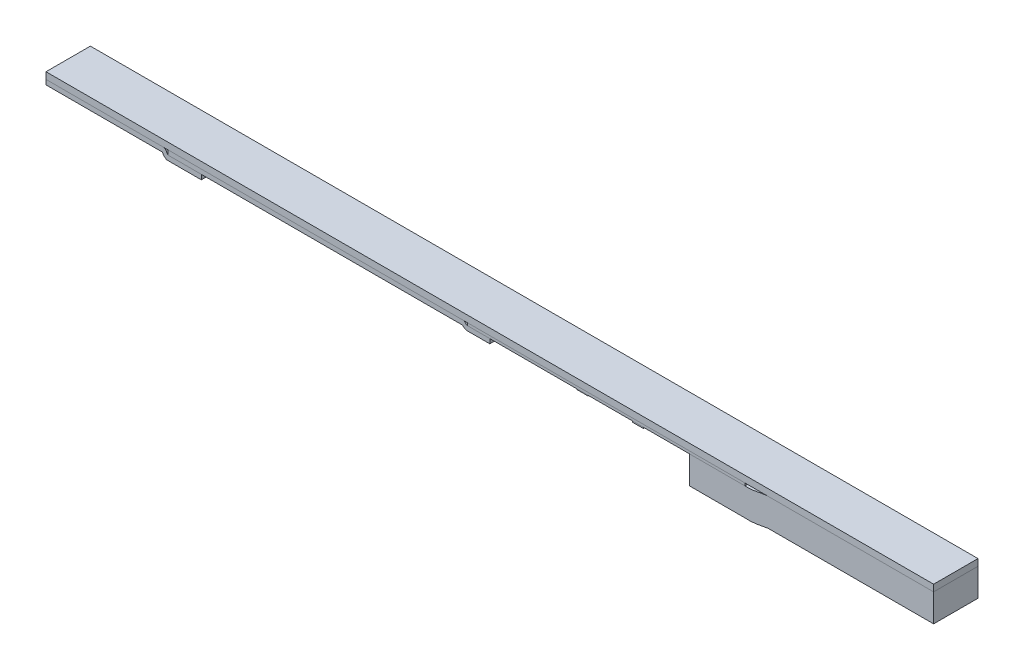
SolidWorks part; units mm, degrees
other "ExplView1" [suppressed]
other "Explode Step1" [suppressed]
other "Explode Line1"
other "Explode Step2" [suppressed]
other "Explode Line1"
other "Explode Line2"
other "Explode Step3" [suppressed]
other "Explode Line1"
other "Explode Step4" [suppressed]
other "Explode Line1"
other "Explode Step5" [suppressed]
other "Explode Line1"
other "Explode Line2"
other "Explode Line3"
ref_plane "Front" through (0, 0, 0) normal (0, 0, 1) x (1, 0, 0)
ref_plane "Top" through (0, 0, 0) normal (0, 1, 0) x (1, 0, 0)
ref_plane "Right" through (0, 0, 0) normal (1, 0, 0) x (0, 0, -1)
sketch "Sketch1" plane through (0, 0, 0) normal (0, 1, 0) x (1, 0, 0)
  line L1 (-40, -2) -> (40, -2)
  line L2 (-40, -2) -> (-40, 2)
  line L3 (-40, 2) -> (40, 2)
  line L4 (40, -2) -> (40, 2)
  line L5 (-40, -2) -> (40, 2) construction
  line L6 (-40, 2) -> (40, -2) construction
  point P0 (0, 0)
  dimension "D1" = 80
  dimension "D2" = 4
extrude "80mm backing card" add sketch "Sketch1" along normal blind 0.6
ref_plane "Middle downstream axis strip" through (0, 0, 0) normal (0, 0, 1) x (1, 0, 0)
sketch "Sketch18" plane through (0, 0, 0) normal (0, -1, 0) x (1, 0, 0)
  line L2 (-2, 2) -> (23, 2)
  line L3 (-2, 2) -> (-2, -2)
  line L4 (-2, -2) -> (23, -2)
  line L5 (23, 2) -> (23, -2)
  line L6 (40, -2) -> (-40, -2) construction
  line L7 (40, 2) -> (40, -2) construction
  dimension "D1" = 25
  dimension "D2" = 17
extrude "CN95_25mm_17mm from end" add sketch "Sketch18" along normal blind 0.23 separate body
sketch "Sketch3" plane through (0, 0, 0) normal (0, -1, 0) x (1, 0, 0)
  line L0 (0, 0) -> (19, 0) construction
  line L1 (-6, -2) -> (19, -2)
  line L2 (-6, -2) -> (-6, 2)
  line L3 (-6, 2) -> (19, 2)
  line L4 (19, -2) -> (19, 2)
  line L5 (-6, -2) -> (19, 2) construction
  line L6 (-6, 2) -> (19, -2) construction
  point P0 (10.5, 0)
  dimension "D1" = 10.5
  dimension "D2" = 25
  dimension "D3" = 4
  dimension "D4" = 19
extrude "CN95_25mm" [suppressed] add sketch "Sketch3" along normal blind 0.23 separate body
sketch "Sketch8" [suppressed] plane through (0, 0, 0) normal (0, 0, 1) x (1, 0, 0)
  line L1 (14, -1.03) -> (18.843, -1.03)
  line L2 (14, -1.03) -> (14, -0.23)
  line L3 (19.6805, 0) -> (40, 0)
  line L4 (14, -0.23) -> (19, -0.23)
  line L5 (40, -0.8) -> (40, 0)
  line L6 (19.8592, -0.8) -> (40, -0.8)
  line L8 (14.8, -1.03) -> (18.843, -1.03) construction
  line L9 (19.8592, -0.8) -> (39.2, -0.8) construction
  line L10 (0, 0) -> (14, 0) construction
  line L11 (-6, -0.23) -> (19, -0.23) construction
  line L12 (39.2, -0.8) -> (39.2, -0.8) construction
  line L13 (14.8, -1.03) -> (14.8, -1.03) construction
  spline S0 degree 3 poles (19, -0.23) (19.3285, -0.4198) (19.391, 0.0213) (19.6805, 0) knots 0 0 0 0 1 1 1 1
  spline S1 degree 1 poles (18.843, -1.03) (19.8592, -0.8) knots 0 0 1 1 construction
  spline S2 degree 3 poles (18.843, -1.03) (18.9476, -1.0624) (19.167, -1.0968) (19.5027, -1.0322) (19.7371, -0.9006) (19.8143, -0.8386) (19.8592, -0.8) knots 0.086652 0.086652 0.086652 0.086652 0.182115 0.277578 0.373041 0.468503 0.468503 0.468503 0.468503
  dimension "D1" = 0.8
  dimension "D2" = 14
  dimension "D3" = 0
  dimension "D4" = 21
extrude "C083_26mm" [suppressed] add sketch "Sketch8" against normal up to vertex and the other way up to vertex separate body
sketch "Sketch10" [suppressed] plane through (0, 0, 0) normal (0, 0, 1) x (1, 0, 0)
  line L0 (-4, 0) -> (-29, 0) construction
  line L1 (-6.4051, 0) -> (-29, 0)
  line L2 (-4, -0.23) -> (-6, -0.23)
  line L3 (-4, -0.53) -> (-5.9863, -0.53)
  line L4 (-6.4562, -0.3) -> (-29, -0.3)
  line L5 (-4, -0.53) -> (-4, -0.23)
  line L6 (-6, -0.23) -> (19, -0.23) construction
  line L7 (-29, -0.3) -> (-29, 0)
  spline S0 degree 3 poles (-6, -0.23) (-6.1991, -0.2528) (-6.2203, -0.0102) (-6.4051, 0) knots 0 0 0 0 1 1 1 1
  spline S1 degree 1 poles (-5.9863, -0.53) (-6.4562, -0.3) knots 0 0 1 1 construction
  spline S2 degree 3 poles (-5.9863, -0.53) (-6.1018, -0.5388) (-6.3067, -0.4635) (-6.4147, -0.3458) (-6.4399, -0.3178) (-6.4562, -0.3) knots 0.015374 0.015374 0.015374 0.015374 0.30052 0.443093 0.585666 0.585666 0.585666 0.585666
  dimension "D1" = 25
  dimension "D2" = 0
  dimension "D3" = 2
  dimension "D4" = 0.3
extrude "F5_25mm" [suppressed] add sketch "Sketch10" along normal up to vertex and the other way up to vertex separate body
sketch "Sketch11" plane through (0, 0, 0) normal (0, -1, 0) x (1, 0, 0)
  line L0 (40, -2) -> (-40, -2) construction
  line L1 (-40, 2) -> (-33, 2)
  line L2 (-40, 2) -> (-40, -2)
  line L3 (-40, -2) -> (-33, -2)
  line L4 (-33, 2) -> (-33, -2)
  dimension "D1" = 7
extrude "CN95 sample pad_7mm" [suppressed] add sketch "Sketch11" along normal blind 0.82 separate body
sketch "Sketch12" plane through (0, 0, 0) normal (0, 0, 1) x (1, 0, 0)
  line L0 (0, 0) -> (-32.1741, 0) construction
  line L1 (0, 0) -> (-27, 0) construction
  line L2 (-32.1741, 0) -> (-30.0838, 0)
  line L3 (-27, -1.3) -> (-29, -1.3)
  line L4 (-35, -0.82) -> (-33, -0.82)
  line L5 (-35, -1.56) -> (-32.97, -1.56)
  line L6 (-31.9067, -0.74) -> (-30.2503, -0.74)
  line L7 (-27, -2.04) -> (-29.0406, -2.04)
  line L8 (-35, -1.56) -> (-35, -0.82)
  line L9 (-27, -2.04) -> (-27, -1.3)
  spline S0 degree 3 poles (-33, -0.82) (-32.4851, -0.7782) (-32.6673, -0.0946) (-32.1741, 0) knots 0 0 0 0 1 1 1 1
  spline S1 degree 3 poles (-29, -1.3) (-29.7084, -1.2221) (-29.2786, -0.0898) (-30.0838, 0) knots 0 0 0 0 1 1 1 1
  spline S2 degree 1 poles (-32.97, -1.56) (-31.9067, -0.74) knots 0 0 1 1 construction
  spline S3 degree 1 poles (-29.0406, -2.04) (-30.2503, -0.74) knots 0 0 1 1 construction
  spline S4 degree 3 poles (-32.97, -1.56) (-32.9619, -1.5593) (-32.9526, -1.5587) (-32.8787, -1.5522) (-32.7475, -1.5311) (-32.4851, -1.4502) (-32.1734, -1.22) (-31.9863, -0.9229) (-31.9366, -0.8093) (-31.9067, -0.74) knots -0.019337 -0.019337 -0.019337 -0.019337 -0.003586 0.012164 0.043666 0.106669 0.232675 0.358681 0.484687 0.484687 0.484687 0.484687
  spline S5 degree 3 poles (-30.2503, -0.74) (-30.2392, -0.7763) (-30.2216, -0.8412) (-30.1686, -1.0392) (-30.0916, -1.2954) (-29.8973, -1.6109) (-29.6588, -1.8425) (-29.3828, -1.9746) (-29.1974, -2.0206) (-29.0668, -2.0376) (-29.0537, -2.0386) (-29.0406, -2.04) knots -0.018979 -0.018979 -0.018979 -0.018979 0.054899 0.128777 0.276534 0.350412 0.424291 0.498169 0.535108 0.553578 0.572048 0.572048 0.572048 0.572048
  dimension "D1" = 0.74
  dimension "D2" = 27
  dimension "D3" = 1.3
  dimension "D4" = 2
  dimension "D6" = 2
extrude "Shunt" [suppressed] add sketch "Sketch12" along normal up to vertex and the other way up to vertex separate body
sketch "Sketch13" [suppressed] plane through (0, 0, 0) normal (0, 0, 1) x (1, 0, 0)
  line L0 (-29, -0.3) -> (-6.4562, -0.3) construction
  line L1 (0, 0) -> (-26, 0) construction
  line L2 (-26, -0.64) -> (-29.1253, -0.64)
  line L3 (-40, -0.34) -> (-29.4516, -0.34)
  line L4 (-40, 0) -> (-29.3869, 0)
  line L5 (-29.3869, 0) -> (-40, 0) construction
  line L6 (-26, -0.3) -> (-29, -0.3)
  line L7 (-26, -0.64) -> (-26, -0.3)
  line L8 (-40, -0.34) -> (-40, 0)
  spline S0 degree 3 poles (-29, -0.3) (-29.1238, -0.1944) (-29.2189, -0.0439) (-29.3869, 0) knots 0 0 0 0 1 1 1 1
  spline S1 degree 1 poles (-29.1253, -0.64) (-29.4516, -0.34) knots 0 0 1 1 construction
  spline S2 degree 3 poles (-29.1253, -0.64) (-29.1555, -0.6142) (-29.2081, -0.572) (-29.3337, -0.4528) (-29.4092, -0.3732) (-29.434, -0.352) (-29.4516, -0.34) knots -0.25657 -0.25657 -0.25657 -0.25657 -0.012563 0.231444 0.475452 0.719459 0.719459 0.719459 0.719459
  dimension "D1" = 26
  dimension "D2" = 14
  dimension "D3" = 0
  dimension "D4" = 3
  dimension "D5" = 0.34
extrude "CF3_14mm" [suppressed] add sketch "Sketch13" along normal up to vertex and the other way up to vertex separate body
ref_plane "Plane2" through (0, 0, 0) normal (1, 0, 0) x (0, 0, -1)
sketch "Sketch16" plane through (0, 0, 0) normal (0, 0, 1) x (1, 0, 0)
  line L0 (0, 0) -> (-26, 0) construction
  line L1 (-26, 0) -> (-26, -0.41) construction
  line L2 (-26, -0.41) -> (-29, -0.41)
  line L3 (-40, 0) -> (-29.42, 0)
  line L4 (-40, -0.43) -> (-29.5129, -0.43)
  line L5 (-26, -0.84) -> (-29.149, -0.84)
  line L6 (-40, -0.43) -> (-40, 0)
  line L7 (-26, -0.84) -> (-26, -0.41)
  spline S0 degree 3 poles (-29, -0.41) (-29.157, -0.2864) (-29.1646, 0.0012) (-29.42, 0) knots 0 0 0 0 1 1 1 1
  spline S1 degree 1 poles (-29.149, -0.84) (-29.5129, -0.43) knots 0 0 1 1 construction
  spline S2 degree 3 poles (-29.5129, -0.43) (-29.493, -0.4661) (-29.4596, -0.5264) (-29.3746, -0.6553) (-29.2481, -0.7632) (-29.218, -0.7849) (-29.1737, -0.8205) (-29.149, -0.84) knots -0.248578 -0.248578 -0.248578 -0.248578 -0.091181 0.066215 0.144914 0.223612 0.381008 0.381008 0.381008 0.381008
  dimension "D1" = 26
  dimension "D2" = 0.41
  dimension "D3" = 3
  dimension "D4" = 10.58
  dimension "D5" = 40
  dimension "D6" = 0.43
extrude "CF4_14mm" add sketch "Sketch16" along normal up to vertex and the other way up to vertex separate body
sketch "Sketch17" plane through (0, 0, 0) normal (0, 0, 1) x (1, 0, 0)
  line L0 (0, 0) -> (18, 0) construction
  line L1 (25, 0) -> (40, 0)
  line L2 (18, 0) -> (18, -0.185) construction
  line L3 (18, -0.185) -> (23, -0.185)
  line L4 (18, -2.685) -> (22.7601, -2.685)
  line L5 (25.0293, -2.5) -> (40, -2.5)
  line L6 (18, -2.685) -> (18, -0.185)
  line L7 (40, -2.5) -> (40, 0)
  spline S0 degree 3 poles (23, -0.185) (23.6752, -0.3602) (24.3288, -0.0019) (25, 0) knots 0 0 0 0 1 1 1 1
  spline S1 degree 1 poles (22.7601, -2.685) (25.0293, -2.5) knots 0 0 1 1 construction
  spline S2 degree 3 poles (22.7601, -2.685) (22.9258, -2.7107) (23.275, -2.741) (23.8617, -2.7229) (24.4384, -2.6271) (24.7976, -2.5436) (24.9779, -2.5078) (25.0069, -2.503) (25.0293, -2.5) knots 0.070736 0.070736 0.070736 0.070736 0.168218 0.2657 0.460665 0.655629 0.753112 0.850594 0.850594 0.850594 0.850594
  dimension "D1" = 18
  dimension "D2" = 15
  dimension "D3" = 40
  dimension "D4" = 0.185
  dimension "D5" = 5
  dimension "D6" = 2.5
extrude "Alstrohm 320_22mm_w HF90" [suppressed] add sketch "Sketch17" along normal up to vertex and the other way up to vertex separate body
sketch "Sketch19" plane through (0, 0, 0) normal (0, 0, 1) x (1, 0, 0)
  line L0 (0, 0) -> (-29, 0) construction
  line L1 (0, 0) -> (0, -0.23) construction
  line L2 (0, -0.23) -> (-2, -0.23)
  line L3 (-29, 0) -> (-2.3642, 0)
  line L4 (0, -0.64) -> (-2.0338, -0.64)
  line L5 (-29, -0.41) -> (-2.4794, -0.41)
  line L6 (0, -0.64) -> (0, -0.23)
  line L7 (-29, -0.41) -> (-29, 0)
  spline S0 degree 3 poles (-2, -0.23) (-2.1507, -0.205) (-2.2224, -0.046) (-2.3642, 0) knots 0 0 0 0 1 1 1 1
  spline S1 degree 1 poles (-2.0338, -0.64) (-2.4794, -0.41) knots 0 0 1 1 construction
  spline S2 degree 3 poles (-2.0338, -0.64) (-2.0473, -0.6378) (-2.0578, -0.6377) (-2.2098, -0.6021) (-2.3207, -0.5396) (-2.4258, -0.4595) (-2.4586, -0.4286) (-2.4794, -0.41) knots -0.073801 -0.073801 -0.073801 -0.073801 0.00573 0.085261 0.244322 0.403384 0.562446 0.562446 0.562446 0.562446
  dimension "D1" = 29
  dimension "D2" = 0.23
  dimension "D3" = 2
  dimension "D4" = 26.6358
  dimension "D5" = 0.41
extrude "GFDX_29mm" add sketch "Sketch19" along normal up to vertex and the other way up to vertex separate body
fillet "Fillet2" [suppressed] radius 0.254
sketch "Sketch20" [suppressed] plane through (0, -0.43, 0) normal (0, -1, 0) x (1, 0, 0)
  text T0 "CF4" font "Century Gothic" height in points 10
extrude "Cut-Extrude1" [suppressed] cut sketch "Sketch20" against normal blind 0.0254
sketch "Sketch21" [suppressed] plane through (0, -0.41, 0) normal (0, -1, 0) x (1, 0, 0)
  text T0 "GFDX" font "Century Gothic" height in points 10
extrude "Cut-Extrude2" [suppressed] cut sketch "Sketch21" against normal blind 0.0254
sketch "Sketch22" [suppressed] plane through (0, -0.23, 0) normal (0, -1, 0) x (1, 0, 0)
  text T0 "CN95" font "Century Gothic" height in points 10
extrude "Cut-Extrude3" [suppressed] cut sketch "Sketch22" against normal blind 0.0254
sketch "Sketch23" [suppressed] plane through (0, -2.5, 0) normal (0, -1, 0) x (1, 0, 0)
  text T0 "A320" font "Century Gothic" height in points 10
extrude "Cut-Extrude4" [suppressed] cut sketch "Sketch23" against normal blind 0.0254
sketch "Sketch24" plane through (0, 0, 0) normal (0, -1, 0) x (1, 0, 0)
  line L0 (-40, 2) -> (40, 2) construction
  line L1 (1, 2) -> (23, 2)
  line L2 (1, 2) -> (1, -2)
  line L3 (1, -2) -> (23, -2)
  line L4 (23, 2) -> (23, -2)
  line L5 (40, -2) -> (-40, -2) construction
  dimension "D1" = 23
  dimension "D2" = 22
extrude "HF90_22mm" [suppressed] add sketch "Sketch24" along normal blind 0.185 separate body
sketch "Sketch25" plane through (0, 0, 0) normal (0, -1, 0) x (1, 0, 0)
  line L0 (40, -2) -> (-40, -2) construction
  line L1 (-7, -2) -> (23, -2)
  line L2 (-7, -2) -> (-7, 2)
  line L3 (-7, 2) -> (23, 2)
  line L4 (23, -2) -> (23, 2)
  line L5 (-40, 2) -> (40, 2) construction
  line L6 (40, 2) -> (40, -2) construction
  dimension "D1" = 17
  dimension "D2" = 30
extrude "HF90_30mm" [suppressed] add sketch "Sketch25" along normal blind 0.185 separate body
sketch "Sketch26" plane through (0, 0, 0) normal (0, -1, 0) x (1, 0, 0)
  line L0 (-40, 2) -> (40, 2) construction
  line L1 (-20, 2) -> (23, 2)
  line L2 (-20, 2) -> (-20, -2)
  line L3 (-20, -2) -> (23, -2)
  line L4 (23, 2) -> (23, -2)
  line L5 (40, -2) -> (-40, -2) construction
  line L6 (40, 2) -> (40, -2) construction
  dimension "D1" = 17
  dimension "D2" = 43
extrude "HF90_43mm" [suppressed] add sketch "Sketch26" along normal blind 0.185 separate body
sketch "Sketch27" plane through (0, 0, 0) normal (0, 0, 1) x (1, 0, 0)
  line L0 (18, 0) -> (18, -0.185) construction
  line L1 (0, 0) -> (18, 0) construction
  line L2 (25, 0) -> (40, 0)
  line L3 (18, -0.185) -> (23, -0.185)
  line L4 (18, -1.485) -> (22.9357, -1.485)
  line L5 (24.978, -1.3) -> (40, -1.3)
  line L6 (18, -1.485) -> (18, -0.185)
  line L7 (40, -1.3) -> (40, 0)
  spline S0 degree 3 poles (23, -0.185) (23.6767, -0.2619) (24.3243, 0.0229) (25, 0) knots 0 0 0 0 1 1 1 1
  spline S1 degree 1 poles (22.9357, -1.485) (24.978, -1.3) knots 0 0 1 1 construction
  spline S2 degree 3 poles (22.9357, -1.485) (23.0661, -1.4965) (23.3381, -1.5033) (23.8045, -1.4679) (24.2882, -1.3818) (24.7237, -1.3052) (24.8821, -1.2968) (24.978, -1.3) knots 0.024555 0.024555 0.024555 0.024555 0.147843 0.271131 0.517708 0.764284 1.010861 1.010861 1.010861 1.010861
  dimension "D1" = 18
  dimension "D2" = 0.185
  dimension "D3" = 40
  dimension "D4" = 15
  dimension "D5" = 5
  dimension "D6" = 1.3
extrude "CF6_22mm" [suppressed] add sketch "Sketch27" along normal up to vertex and the other way up to vertex separate body
sketch "Sketch28" plane through (0, 0, 0) normal (0, 0, 1) x (1, 0, 0)
  line L0 (-3, 0) -> (-34, 0) construction
  line L1 (-3, 0) -> (0, 0) construction
  line L2 (0, 0) -> (0, -0.185) construction
  line L3 (-3, 0) -> (-40.005, 0)
  line L4 (0, -0.185) -> (-2, -0.185)
  line L5 (-3.0394, -0.43) -> (-40.0444, -0.43)
  line L6 (0, -0.615) -> (-2.0394, -0.615)
  line L7 (-40.0444, -0.43) -> (-40.005, 0)
  line L8 (0, -0.615) -> (0, -0.185)
  line L12 (0, -0.615) -> (-34, -0.615) construction
  spline S0 degree 3 poles (-2, -0.185) (-2.3547, -0.2434) (-2.6483, 0.0177) (-3, 0) knots 0 0 0 0 1 1 1 1
  spline S2 degree 3 poles (-2.0394, -0.615) (-2.1627, -0.6249) (-2.4318, -0.595) (-2.7009, -0.5011) (-2.9115, -0.4356) (-2.9916, -0.4278) (-3.0394, -0.43) knots 0.014089 0.014089 0.014089 0.014089 0.262877 0.511665 0.760453 1.009241 1.009241 1.009241 1.009241
  dimension "D1" = 37.005
  dimension "D2" = 37.005
  dimension "D3" = 0.185
  dimension "D4" = 2
extrude "GFDX_34mm" [suppressed] add sketch "Sketch28" along normal up to vertex and the other way up to vertex separate body
sketch "Sketch29" plane through (0, 0, 0) normal (0, 0, 1) x (1, 0, 0)
  line L0 (0, 0) -> (-29, 0) construction
  line L1 (-29, 0) -> (-29, -0.43) construction
  line L2 (-29, -0.43) -> (-31, -0.43)
  line L3 (-40, 0) -> (-32, 0)
  line L4 (-40, -0.43) -> (-31.9896, -0.43)
  line L5 (-29, -0.86) -> (-31.0226, -0.86)
  line L6 (-40, -0.43) -> (-40, 0)
  line L7 (-29, -0.86) -> (-29, -0.43)
  spline S0 degree 3 poles (-31, -0.43) (-31.3846, -0.3895) (-31.5958, 0.0196) (-32, 0) knots 0 0 0 0 1 1 1 1
  spline S1 degree 1 poles (-31.0226, -0.86) (-31.9896, -0.43) knots 0 0 1 1 construction
  spline S2 degree 3 poles (-31.9896, -0.43) (-31.9594, -0.4285) (-31.9186, -0.43) (-31.7494, -0.5326) (-31.5256, -0.7006) (-31.2894, -0.8061) (-31.1568, -0.8413) (-31.0657, -0.8559) (-31.0385, -0.8583) (-31.0226, -0.86) knots -0.019479 -0.019479 -0.019479 -0.019479 0.237539 0.494558 0.751576 0.880086 0.94434 0.976467 1.008595 1.008595 1.008595 1.008595
  dimension "D1" = 29
  dimension "D2" = 0.43
  dimension "D3" = 2
  dimension "D4" = 8
  dimension "D5" = 40
  dimension "D6" = 0.43
extrude "CF4_11mm" [suppressed] add sketch "Sketch29" along normal up to vertex and the other way up to vertex separate body
sketch "Sketch33" [suppressed] plane through (0, -0.86, 0) normal (0, -1, 0) x (1, 0, 0)
  line L1 (-31.0226, 2) -> (-29, 2)
  line L2 (-31.0226, 2) -> (-31.0226, -2)
  line L3 (-31.0226, -2) -> (-29, -2)
  line L4 (-29, 2) -> (-29, -2)
extrude "CF4_11mm extra height" [suppressed] add sketch "Sketch33" along normal blind 0.07 separate body
sketch "Sketch31" plane through (0, 0, 0) normal (0, 0, 1) x (1, 0, 0)
  line L0 (-7.4111, 0) -> (-31, 0) construction
  line L1 (0, 0) -> (3, 0) construction
  line L2 (3, 0) -> (3, -0.185) construction
  line L3 (3, -0.185) -> (-7, -0.185)
  line L4 (3, -0.615) -> (-6.9785, -0.615)
  line L5 (-7.4111, 0) -> (-31, 0)
  line L6 (-7.5139, -0.43) -> (-31, -0.43)
  line L7 (3, -0.615) -> (3, -0.185)
  line L8 (-31, 0) -> (-31, -0.43)
  line L12 (3, -0.595) -> (-31, -0.595) construction
  spline S0 degree 3 poles (-7, -0.185) (-7.1747, -0.2081) (-7.2605, -0.0401) (-7.4111, 0) knots 0 0 0 0 1 1 1 1
  spline S1 degree 1 poles (-6.9785, -0.615) (-7.5139, -0.43) knots 0 0 1 1 construction
  spline S2 degree 3 poles (-6.9785, -0.615) (-7.1005, -0.6248) (-7.3163, -0.5687) (-7.4553, -0.4731) (-7.4918, -0.4463) (-7.5139, -0.43) knots 0.025175 0.025175 0.025175 0.025175 0.321643 0.469877 0.618112 0.618112 0.618112 0.618112
  dimension "D1" = 31
  dimension "D2" = 3
  dimension "D3" = 0.185
  dimension "D4" = 10
  dimension "D5" = 0.43
  dimension "D8" = 34
extrude "GFDX_34mm_v2" [suppressed] add sketch "Sketch31" along normal up to vertex and the other way up to vertex separate body
sketch "Sketch32" plane through (0, 0, 0) normal (0, 0, 1) x (1, 0, 0)
  line L0 (0, 0) -> (-18, 0) construction
  line L1 (-18, 0) -> (-18, -0.185) construction
  line L2 (-18, -0.185) -> (-20, -0.185)
  line L3 (-31, 0) -> (-21, 0)
  line L4 (-31, -0.43) -> (-20.9805, -0.43)
  line L5 (-18, -0.615) -> (-19.9907, -0.615)
  line L6 (-18, -0.615) -> (-18, -0.185)
  line L7 (-31, -0.43) -> (-31, 0)
  spline S0 degree 3 poles (-20, -0.185) (-20.3499, -0.2021) (-20.6468, 0.032) (-21, 0) knots 0 0 0 0 1 1 1 1
  spline S1 degree 1 poles (-19.9907, -0.615) (-20.9805, -0.43) knots 0 0 1 1 construction
  spline S2 degree 3 poles (-20.9805, -0.43) (-20.9342, -0.4258) (-20.8545, -0.4276) (-20.6541, -0.4862) (-20.3868, -0.5808) (-20.1156, -0.6198) (-19.9907, -0.615) knots 0.007041 0.007041 0.007041 0.007041 0.259852 0.512664 0.765475 1.018286 1.018286 1.018286 1.018286
  dimension "D1" = 18
  dimension "D2" = 0.185
  dimension "D3" = 2
  dimension "D4" = 31
  dimension "D5" = 10
  dimension "D6" = 0.43
extrude "GFDX_13mm" [suppressed] add sketch "Sketch32" along normal up to vertex and the other way up to vertex separate body
sketch "Sketch35" [suppressed] plane through (0, -0.185, 0) normal (0, -1, 0) x (1, 0, 0)
  line L0 (23, 2) -> (-20, 2) construction
  line L1 (7.67, -2) -> (8.67, -2)
  line L2 (7.67, -2) -> (7.67, 2)
  line L3 (7.67, 2) -> (8.67, 2)
  line L4 (8.67, -2) -> (8.67, 2)
  line L5 (7.67, -2) -> (8.67, 2) construction
  line L6 (7.67, 2) -> (8.67, -2) construction
  line L8 (12.85, -2) -> (13.85, -2)
  line L9 (12.85, -2) -> (12.85, 2)
  line L10 (12.85, 2) -> (13.85, 2)
  line L11 (13.85, -2) -> (13.85, 2)
  line L12 (12.85, -2) -> (13.85, 2) construction
  line L13 (12.85, 2) -> (13.85, -2) construction
  point P0 (8.17, 0)
  point P7 (13.35, 0)
  point P13 (12.85, 0)
  dimension "D1" = 1
  dimension "D2" = 8.17
  dimension "D3" = 13.35
  dimension "D4" = 1
extrude "Test and Control Lines" [suppressed] add sketch "Sketch35" along normal blind 0.1 separate body
sketch "Sketch36" plane through (0, 0, 0) normal (0, 0, 1) x (1, 0, 0)
  line L0 (0, 0) -> (18, 0) construction
  line L1 (25, 0) -> (40, 0)
  line L2 (18, 0) -> (18, -0.23) construction
  line L3 (18, -0.23) -> (23, -0.23)
  line L4 (18, -2.73) -> (22.8884, -2.73)
  line L5 (25.0818, -2.5) -> (40, -2.5)
  line L6 (18, -2.73) -> (18, -0.23)
  line L7 (40, -2.5) -> (40, 0)
  spline S0 degree 3 poles (23, -0.23) (23.6789, -0.3057) (24.3282, -0.0309) (25, 0) knots 0 0 0 0 1 1 1 1
  spline S1 degree 1 poles (22.8884, -2.73) (25.0818, -2.5) knots 0 0 1 1 construction
  spline S2 degree 3 poles (22.8884, -2.73) (23.0417, -2.7415) (23.3623, -2.7484) (23.9022, -2.7112) (24.4476, -2.6187) (24.8093, -2.5428) (25.0055, -2.5093) (25.052, -2.5031) (25.0818, -2.5) knots 0.036879 0.036879 0.036879 0.036879 0.146505 0.25613 0.47538 0.694631 0.804256 0.913882 0.913882 0.913882 0.913882
  dimension "D1" = 18
  dimension "D2" = 15
  dimension "D3" = 40
  dimension "D4" = 0.23
  dimension "D5" = 5
  dimension "D6" = 2.5
extrude "Alstrohm 320_22mm_w CN95" add sketch "Sketch36" along normal up to vertex and the other way up to vertex separate body
sketch "Sketch37" [suppressed] plane through (0, 0, 0) normal (0, -1, 0) x (1, 0, 0)
  line L0 (-40, 2) -> (40, 2) construction
  line L1 (-22.0002, 2) -> (22.9998, 2)
  line L2 (-22.0002, 2) -> (-22.0002, -2)
  line L3 (-22.0002, -2) -> (22.9998, -2)
  line L4 (22.9998, 2) -> (22.9998, -2)
  line L5 (40, -2) -> (-40, -2) construction
  line L6 (40, 2) -> (40, -2) construction
  dimension "D1" = 17.0002
  dimension "D2" = 45
extrude "HF90_45mm" [suppressed] add sketch "Sketch37" along normal blind 0.185 separate body
ref_plane "Plane3" through (0, -0.185, 0) normal (0, -1, 0) x (-1, 0, 0)
sketch "Sketch38" plane through (0, -0.185, 0) normal (0, -1, 0) x (-1, 0, 0)
  line L2 (-7.849, -2) -> (-8.849, -2)
  line L3 (-7.849, -2) -> (-7.849, 2)
  line L4 (-7.849, 2) -> (-8.849, 2)
  line L5 (-8.849, -2) -> (-8.849, 2)
  line L6 (-7.849, -2) -> (-8.849, 2) construction
  line L7 (-7.849, 2) -> (-8.849, -2) construction
  point P0 (-8.349, 0)
  dimension "D1" = 1
  dimension "D3" = 4
  dimension "D6" = 8.349
extrude "Test Line" add sketch "Sketch38" along normal blind 0.1 separate body
sketch "Sketch39" [suppressed] plane through (0, 0, 0) normal (0, 0, 1) x (1, 0, 0)
  line L0 (0, 0) -> (-20, 0) construction
  line L1 (-20, 0) -> (-20, -0.185) construction
  line L2 (-20, -0.185) -> (-22, -0.185)
  line L3 (-31, 0) -> (-23, 0)
  line L4 (-20, -0.615) -> (-21.9741, -0.615)
  line L5 (-31, -0.43) -> (-22.9695, -0.43)
  line L6 (-20, -0.615) -> (-20, -0.185)
  line L7 (-31, -0.43) -> (-31, 0)
  spline S0 degree 3 poles (-22, -0.185) (-22.3571, -0.2348) (-22.6398, 0.0513) (-23, 0) knots 0 0 0 0 1 1 1 1
  spline S1 degree 1 poles (-21.9741, -0.615) (-22.9695, -0.43) knots 0 0 1 1 construction
  spline S2 degree 3 poles (-21.9741, -0.615) (-22.1098, -0.6294) (-22.4127, -0.591) (-22.6822, -0.4785) (-22.8399, -0.43) (-22.8975, -0.423) (-22.9283, -0.4245) (-22.9318, -0.4246) (-22.9591, -0.4285) (-22.9695, -0.43) knots 0.018385 0.018385 0.018385 0.018385 0.270766 0.523147 0.775527 0.901717 0.964812 0.99636 1.027908 1.027908 1.027908 1.027908
  dimension "D1" = 20
  dimension "D2" = 0.185
  dimension "D3" = 31
  dimension "D4" = 8
  dimension "D5" = 0.43
extrude "GFDX_11mm" [suppressed] add sketch "Sketch39" along normal up to vertex and the other way up to vertex separate body
sketch "Sketch40" plane through (0, -0.23, 0) normal (0, -1, 0) x (1, 0, 0)
  line L6 (-2, -2) -> (23, -2) construction
  line L7 (12.8499, 2) -> (13.8506, 2)
  line L8 (12.8499, 2) -> (12.8499, -2)
  line L9 (12.8499, -2) -> (13.8506, -2)
  line L10 (13.8506, 2) -> (13.8506, -2)
  line L11 (12.8499, 2) -> (13.8506, -2) construction
  line L12 (12.8499, -2) -> (13.8506, 2) construction
  line L14 (0, 0) -> (0, 8.7829) construction
  point P0 (13.3502, 0)
  dimension "D1" = 1.0008
extrude "Control Line" add sketch "Sketch40" along normal blind 0.1 separate body
ref_plane "Plane4" through (-2, 0, 0) normal (-1, 0, 0) x (0, 0, 1)
ref_plane "Plane5" through (-40, 0, 0) normal (-1, 0, 0) x (0, 0, 1)
sketch "Sketch41" [suppressed] plane through (0, -0.43, 0) normal (0, -1, 0) x (1, 0, 0)
  line L0 (-40.0444, -2) -> (-3.0394, -2) construction
  line L1 (-40.0444, 2) -> (-29.8937, 2)
  line L2 (-40.0444, 2) -> (-40.0444, -2)
  line L3 (-40.0444, -2) -> (-29.8937, -2)
  line L4 (-29.8937, 2) -> (-29.8937, -2)
extrude "Boss-Extrude1" [suppressed] add sketch "Sketch41" along normal blind 0.1 separate body
sketch "Sketch42" [suppressed] plane through (0, 0, 0) normal (0, 0, 1) x (1, 0, 0)
  line L0 (0, 0) -> (-6, 0) construction
  line L1 (-6, 0) -> (19, 0)
  line L2 (-6, -0.23) -> (19, -0.23)
  line L3 (-6, -0.23) -> (-6, 0)
  line L4 (19, -0.23) -> (19, 0)
  dimension "D1" = 6
  dimension "D2" = 25
  dimension "D3" = 0.23
extrude "CN95 Inline Plasma Sep" [suppressed] add sketch "Sketch42" along normal mid plane 4 separate body
sketch "Sketch43" [suppressed] plane through (0, 0, 0) normal (0, 0, 1) x (1, 0, 0)
  line L0 (0, 0) -> (-8, 0) construction
  line L1 (0, 0) -> (3, 0) construction
  line L2 (-8, 0) -> (-6.2795, 0)
  line L3 (2.9912, -0.2293) -> (-6.0088, -0.2293)
  line L4 (-8, -0.41) -> (-6.5307, -0.41)
  line L5 (2.9912, -0.6393) -> (-5.9959, -0.6393)
  line L6 (-8, 0) -> (-8, -0.41)
  line L7 (2.9912, -0.2293) -> (2.9912, -0.6393)
  arc A0 (-6.0088, -0.2293) -> (-6.2795, 0) centre (-6.0295, 0.0207) cw
  arc A1 (-5.9959, -0.6393) -> (-6.5307, -0.41) centre (-6.0295, 0.0207) cw
  dimension "D1" = 8
  dimension "D2" = 3
  dimension "D3" = 9
  dimension "D4" = 0.41
extrude "8951 Pad Beneath" [suppressed] add sketch "Sketch43" along normal mid plane 4 separate body
sketch "Sketch44" [suppressed] plane through (0, 0, 0) normal (0, 0, 1) x (1, 0, 0)
  line L0 (0.0079, -0.0002) -> (-25.9921, -0.0002) construction
  line L1 (-25.9921, -0.3482) -> (-8.7153, -0.3482)
  line L10 (-25.9921, -0.0002) -> (-8.4961, -0.0002)
  line L11 (-6.5412, -0.4102) -> (-7.7463, -0.4102)
  line L12 (-6.7298, -0.7582) -> (-7.7021, -0.7582)
  line L13 (-25.9921, -0.0002) -> (-25.9921, -0.3482)
  line L14 (-6, -0.64) -> (-5.8697, -0.9627)
  arc A4 (-7.7463, -0.4102) -> (-8.4961, -0.0002) centre (-7.9162, 0.1697) cw
  arc A7 (-6, -0.64) -> (-6.5412, -0.4102) centre (-6.1557, -0.2545) cw
  arc A8 (-7.7021, -0.7582) -> (-8.7153, -0.3482) centre (-7.9162, 0.1697) cw
  arc A9 (-5.8697, -0.9627) -> (-6.7298, -0.7582) centre (-6.1557, -0.2545) cw
  dimension "D1" = 26
  dimension "D2" = 0.348
extrude "Vivid inline pad_20mm" [suppressed] add sketch "Sketch44" along normal mid plane 4 separate body
sketch "Sketch45" [suppressed] plane through (0, 0, 0) normal (0, 0, 1) x (1, 0, 0)
  line L0 (0, 0) -> (-40, 0) construction
  line L1 (0, 0) -> (-15, 0) construction
  line L12 (-40, 0) -> (-40, -0.348)
  line L13 (-25.4546, -0.348) -> (-15, -0.348)
  line L14 (-40, 0) -> (-26.476, 0)
  line L16 (-40, -0.348) -> (-26.6663, -0.348)
  line L17 (-25.3816, -0.696) -> (-15, -0.696)
  line L19 (-15, -0.348) -> (-15, -0.696)
  line L20 (-39.652, -0.348) -> (-39.652, -0.41) construction
  line L21 (-39.652, -0.348) -> (-26.6663, -0.348) construction
  line L22 (-40, 0) -> (-40, -0.41) construction
  arc A0 (-25.4546, -0.348) -> (-26.476, 0) centre (-25.7913, 0.3367) cw
  arc A1 (-25.3816, -0.696) -> (-26.6663, -0.348) centre (-25.7913, 0.3367) cw
  dimension "D1" = 40
extrude "8951 Top Pad" [suppressed] add sketch "Sketch45" along normal mid plane 4 separate body
sketch "Sketch46" [suppressed] plane through (0, 0, 0) normal (0, 0, 1) x (1, 0, 0)
  line L0 (0, 0) -> (8, 0) construction
  line L1 (8, 0) -> (13, 0) construction
  line L2 (7.5, -0.23) -> (8.5, -0.23)
  line L3 (12.5, -0.23) -> (13.5, -0.23)
  line L4 (7.5, -0.33) -> (8.5, -0.33)
  line L5 (12.5, -0.33) -> (13.5, -0.33)
  line L6 (7.5, -0.23) -> (7.5, -0.33)
  line L7 (8.5, -0.23) -> (8.5, -0.33)
  line L8 (12.5, -0.23) -> (12.5, -0.33)
  line L9 (13.5, -0.23) -> (13.5, -0.33)
  point P7 (8, -0.23)
  point P10 (13, -0.23)
  dimension "D1" = 8
  dimension "D2" = 5
  dimension "D3" = 1
  dimension "D4" = 1
  dimension "D5" = 0.1
extrude "TL/CL for Inline Separation" [suppressed] add sketch "Sketch46" along normal mid plane 4 separate body
sketch "CN95_55mm" [suppressed] plane through (0, 0, 0) normal (0, 0, 1) x (1, 0, 0)
  line L0 (0, 0) -> (-31, 0) construction
  line L1 (-31, 0) -> (24, 0)
  line L2 (-31, -0.23) -> (24, -0.23)
  line L3 (-31, 0) -> (-31, -0.23)
  line L4 (24, 0) -> (24, -0.23)
  dimension "D1" = 31
  dimension "D2" = 55
  dimension "D3" = 0.23
extrude "CN95_55 mm" [suppressed] add sketch "CN95_55mm" along normal mid plane 4 separate body
sketch "Sketch48" [suppressed] plane through (0, 0, 0) normal (0, 0, 1) x (1, 0, 0)
  line L0 (0, 0) -> (-33, 0) construction
  line L1 (0, 0) -> (-8, 0) construction
  line L2 (-8, -0.23) -> (-30.6263, -0.23)
  line L3 (-33, 0) -> (-31.2664, 0)
  line L4 (-33, -0.348) -> (-31.4489, -0.348)
  line L5 (-8, -0.578) -> (-30.5593, -0.578)
  line L6 (-33, 0) -> (-33, -0.348)
  line L7 (-8, -0.23) -> (-8, -0.578)
  arc A0 (-31.2664, 0) -> (-30.6263, -0.23) centre (-30.8313, 0.2051) ccw
  arc A1 (-31.4489, -0.348) -> (-30.5593, -0.578) centre (-30.8313, 0.2051) ccw
  dimension "D1" = 33
  dimension "D2" = 0.348
extrude "Vivid_25mm" [suppressed] add sketch "Sketch48" along normal mid plane 4 separate body
sketch "Sketch49" [suppressed] plane through (0, 0, 0) normal (0, 0, 1) x (1, 0, 0)
  line L0 (0, 0) -> (-40, 0) construction
  line L1 (0, 0) -> (-18, 0) construction
  line L2 (-17.9907, -0.5777) -> (-30.3556, -0.5777)
  line L3 (-40, 0) -> (-33.3921, 0)
  line L4 (-40, -0.41) -> (-33.4973, -0.41)
  line L5 (-17.9907, -0.9877) -> (-30.3281, -0.9877)
  line L6 (-40, 0) -> (-40, -0.41)
  line L7 (-17.9907, -0.5777) -> (-17.9907, -0.9877)
  arc A0 (-33.3921, 0) -> (-30.3556, -0.5777) centre (-31.0164, 4.2178) ccw
  arc A1 (-33.4973, -0.41) -> (-30.3281, -0.9877) centre (-31.0164, 4.2178) ccw
  dimension "D1" = 40
  dimension "D2" = 18
  dimension "D3" = 0.41
extrude "8951_25mm" [suppressed] add sketch "Sketch49" along normal mid plane 4 separate body
sketch "Sketch50" [suppressed] plane through (0, 0, 0) normal (0, 0, 1) x (1, 0, 0)
  line L0 (0, 0) -> (18, 0) construction
  line L1 (17.9985, -0.23) -> (23.2748, -0.23)
  line L2 (0, 0) -> (40, 0) construction
  line L3 (40, 0) -> (24.3977, 0)
  line L4 (17.9985, -1.83) -> (22.9286, -1.83)
  line L5 (40, -1.6) -> (24.995, -1.6)
  line L6 (17.9985, -0.23) -> (17.9985, -1.83)
  line L7 (40, 0) -> (40, -1.6)
  arc A0 (23.2748, -0.23) -> (24.3977, 0) centre (23.7212, 0.4465) ccw
  arc A1 (22.9286, -1.83) -> (24.995, -1.6) centre (23.7212, 0.4465) ccw
  dimension "D1" = 18
  dimension "D2" = 40
  dimension "D3" = 1.6
extrude "CF6 wick" [suppressed] add sketch "Sketch50" along normal mid plane 4 separate body
sketch "Sketch51" [suppressed] plane through (0, 0, 0) normal (0, 0, 1) x (1, 0, 0)
  line L0 (0, 0) -> (-40, 0) construction
  line L1 (0, 0) -> (-18, 0) construction
  line L2 (-17.9907, -0.5777) -> (-30.438, -0.5777)
  line L3 (-40, 0) -> (-33.6884, 0)
  line L4 (-40, -1.6) -> (-34.0488, -1.6)
  line L5 (-17.9907, -2.1777) -> (-30.3469, -2.1777)
  line L6 (-40, 0) -> (-40, -1.6)
  line L7 (-17.9907, -0.5777) -> (-17.9907, -2.1777)
  arc A0 (-33.6884, 0) -> (-30.438, -0.5777) centre (-31.1204, 5.0157) ccw
  arc A1 (-34.0488, -1.6) -> (-30.3469, -2.1777) centre (-31.1204, 5.0157) ccw
  dimension "D1" = 40
  dimension "D2" = 18
  dimension "D3" = 1.6
extrude "Boss-Extrude3" [suppressed] add sketch "Sketch51" along normal mid plane 4 separate body
sketch "Sketch52" [suppressed] plane through (0, 0, 0) normal (0, 0, 1) x (1, 0, 0)
  line L0 (0, 0) -> (1.7887, 0) construction
  line L1 (0, 0) -> (-14.1694, 0) construction
  line L2 (-14.1694, 0) -> (-8.6618, 0)
  line L3 (1.7887, -0.64) -> (-5.7093, -0.64)
  line L4 (-14.1694, -0.348) -> (-8.7464, -0.348)
  line L5 (1.7887, -0.988) -> (-5.6995, -0.988)
  line L6 (-14.1694, 0) -> (-14.1694, -0.348)
  line L7 (1.7887, -0.64) -> (1.7887, -0.988)
  arc A0 (-8.6618, 0) -> (-5.7093, -0.64) centre (-6.0324, 4.9995) ccw
  arc A1 (-8.7464, -0.348) -> (-5.6995, -0.988) centre (-6.0324, 4.9995) ccw
  dimension "D1" = 0.348
extrude "Demo_Vivid#2" [suppressed] add sketch "Sketch52" along normal mid plane 4 separate body
sketch "Sketch53" [suppressed] plane through (0, 0, 0) normal (0, 0, 1) x (1, 0, 0)
  line L0 (0, 0) -> (-21.0432, 0) construction
  line L1 (-21.0432, 0) -> (-15.2591, 0)
  line L2 (0, -0.988) -> (-5.8556, -0.988)
  line L3 (-13.7941, -0.348) -> (-9.0816, -0.348)
  line L4 (-21.0432, -0.348) -> (-15.4342, -0.348)
  line L5 (-13.7046, -0.696) -> (-9.1587, -0.696)
  line L6 (0, -1.336) -> (-5.847, -1.336)
  line L7 (-21.0432, 0) -> (-21.0432, -0.348)
  line L8 (0, -0.988) -> (0, -1.336)
  arc A1 (-9.0816, -0.348) -> (-5.8556, -0.988) centre (-6.1938, 5.758) ccw
  arc A3 (-9.1587, -0.696) -> (-5.847, -1.336) centre (-6.1938, 5.758) ccw
  arc A4 (-15.2591, 0) -> (-13.7941, -0.348) centre (-14.349, 0.5735) ccw construction
  arc A5 (-13.7941, -0.348) -> (-15.2591, 0) centre (-13.7941, 2.9095) cw
  arc A6 (-15.4342, -0.348) -> (-13.7046, -0.696) centre (-14.349, 0.5735) ccw construction
  arc A7 (-15.4342, -0.348) -> (-13.7046, -0.696) centre (-13.8074, 3.2655) ccw
  dimension "D1" = 0.348
extrude "Demo_Vivid#1" [suppressed] add sketch "Sketch53" along normal mid plane 4 separate body
sketch "Sketch54" [suppressed] plane through (0, 0, 0) normal (0, 0, 1) x (1, 0, 0)
  line L0 (0, 0) -> (-40, 0) construction
  line L1 (-40, 0) -> (-21.7578, 0)
  line L2 (-20.5323, -0.348) -> (-15.9577, -0.348)
  line L3 (-13.7873, -0.6816) -> (-9.1197, -0.6816)
  line L4 (-5.5328, -1.336) -> (-1.2694, -1.336)
  line L5 (-40, -0.41) -> (-21.8812, -0.41)
  line L6 (-20.5202, -0.758) -> (-16.0291, -0.758)
  line L7 (-13.6873, -0.988) -> (-9.1432, -0.988)
  line L8 (-5.5265, -1.746) -> (-1.2694, -1.746)
  line L9 (-40, 0) -> (-40, -0.41)
  line L10 (-1.2694, -1.336) -> (-1.2694, -1.746)
  line L11 (-13.7171, -0.578) -> (-9.0494, -0.578) construction
  arc A0 (-21.7578, 0) -> (-20.5323, -0.348) centre (-20.6511, 1.5655) ccw
  arc A3 (-21.8812, -0.41) -> (-20.5202, -0.758) centre (-20.6511, 1.5655) ccw
  arc A4 (-16.0291, -0.758) -> (-13.6873, -0.988) centre (-14.3874, 3.9208) ccw
  arc A5 (-9.1432, -0.988) -> (-5.5265, -1.746) centre (-5.767, 6.1137) ccw
  arc A6 (-15.9577, -0.348) -> (-13.7171, -0.578) centre (-14.3874, 3.9208) ccw construction
  arc A7 (-9.0494, -0.578) -> (-5.5328, -1.336) centre (-5.767, 6.1137) ccw construction
  arc A8 (-15.9577, -0.348) -> (-13.7873, -0.6816) centre (-14.0496, 4.8391) ccw
  arc A9 (-5.5328, -1.336) -> (-9.1197, -0.6816) centre (-6.2627, 4.8206) cw
  dimension "D1" = 40
  dimension "D2" = 0.41
extrude "Demo_8951 Pad" [suppressed] add sketch "Sketch54" along normal mid plane 4 separate body
sketch "Sketch55" [suppressed] plane through (0, 0, 0) normal (0, 0, 1) x (1, 0, 0)
  line L0 (0.0122, -0.0003) -> (-39.9878, -0.0003) construction
  line L1 (-39.9878, -0.0003) -> (-15.411, -0.0003)
  line L2 (-13.7243, -0.348) -> (-9.1572, -0.348)
  line L3 (0, -0.988) -> (-5.4523, -0.988)
  line L4 (-39.9878, -0.4103) -> (-15.4859, -0.4103)
  line L5 (-13.732, -0.758) -> (-9.247, -0.758)
  line L6 (0, -1.398) -> (-5.433, -1.398)
  line L7 (-39.9878, -0.0003) -> (-39.9878, -0.4103)
  line L8 (0, -0.988) -> (0, -1.398)
  arc A0 (-15.411, -0.0003) -> (-13.7243, -0.348) centre (-13.5239, 4.8889) ccw
  arc A1 (-5.4523, -0.988) -> (-9.1572, -0.348) centre (-6.1319, 6.1216) cw
  arc A2 (-15.4859, -0.4103) -> (-13.732, -0.758) centre (-13.5239, 4.8889) ccw
  arc A3 (-5.433, -1.398) -> (-9.247, -0.758) centre (-6.1319, 6.1216) cw
  dimension "D1" = 40
  dimension "D2" = 0.41
extrude "Demo_longer 8951 pad" [suppressed] add sketch "Sketch55" along normal mid plane 4 separate body
sketch "Sketch59" [suppressed] plane through (0, 0, 0) normal (0, 0, 1) x (1, 0, 0)
  line L0 (0, 0) -> (24, 0) construction
  line L1 (0, 0) -> (-24, 0) construction
  line L2 (24, 0) -> (-24, 0)
  line L3 (24, -0.23) -> (-24, -0.23)
  line L4 (24, 0) -> (24, -0.23)
  line L5 (-24, 0) -> (-24, -0.23)
  dimension "D1" = 24
  dimension "D2" = 24
  dimension "D3" = 0.23
extrude "48mm CN95" [suppressed] add sketch "Sketch59" along normal mid plane 4 separate body
move or copy body "Body-Move/Copy1" [suppressed] bodies to move or copy 111 copy no translate (0, 0, 9.5766)
move or copy body "Body-Move/Copy2" [suppressed] bodies to move or copy 125 copy no translate (0, 0, 12.1902)
move or copy body "Body-Move/Copy3" [suppressed] bodies to move or copy 122 copy no translate (0, 0, 12.1902)
move or copy body "Body-Move/Copy4" [suppressed] bodies to move or copy 124 copy no translate (0, 0, 6.0104)
move or copy body "Body-Move/Copy8" [suppressed] bodies to move or copy 128 copy no translate (0, 0, 0)
move or copy body "Body-Move/Copy9" [suppressed] bodies to move or copy 129 copy no translate (0, 0, 0)
move or copy body "Body-Move/Copy10" [suppressed] bodies to move or copy 130 copy no translate (0, 0, 0)
move or copy body "Body-Move/Copy11" [suppressed] bodies to move or copy 131 copy no translate (0, 0, 0)
